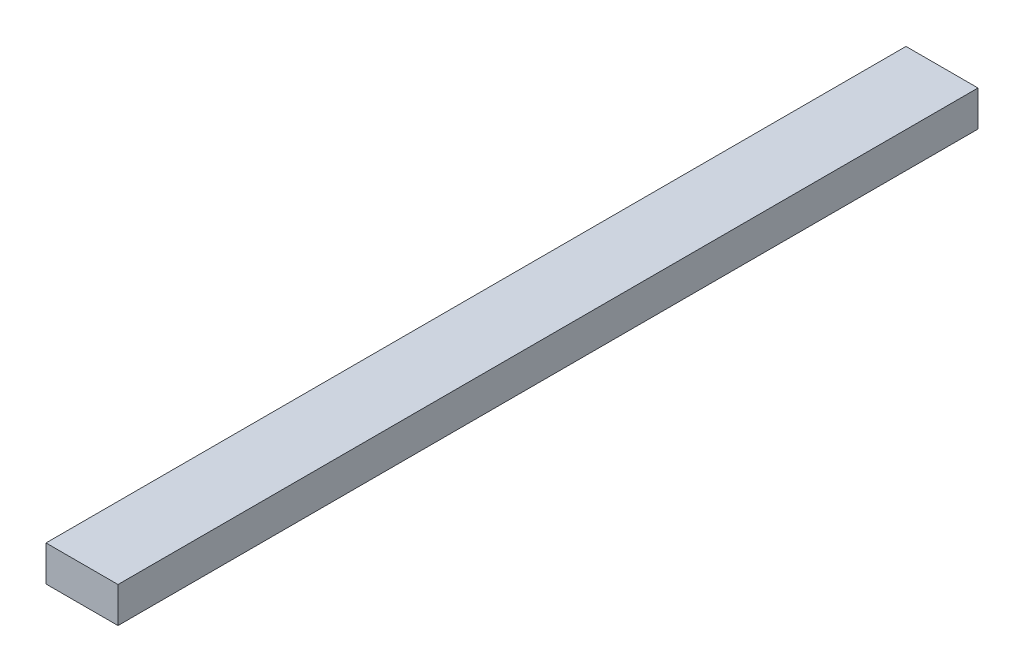
SolidWorks part; units mm, degrees
ref_plane "Front Plane" through (0, 0, 0) normal (0, 0, 1) x (1, 0, 0)
ref_plane "Top Plane" through (0, 0, 0) normal (0, 1, 0) x (1, 0, 0)
ref_plane "Right Plane" through (0, 0, 0) normal (1, 0, 0) x (0, 0, -1)
sketch "Sketch1" plane through (0, 0, 0) normal (0, 0, 1) x (1, 0, 0)
  line L1 (-6.07, -3) -> (6.07, -3)
  line L2 (-6.07, -3) -> (-6.07, 3)
  line L3 (-6.07, 3) -> (6.07, 3)
  line L4 (6.07, -3) -> (6.07, 3)
  line L5 (-6.07, -3) -> (6.07, 3) construction
  line L6 (-6.07, 3) -> (6.07, -3) construction
  point P0 (0, 0)
  dimension "D1" = 6
  dimension "D2" = 12.14
extrude "Boss-Extrude1" add sketch "Sketch1" along normal blind 145
